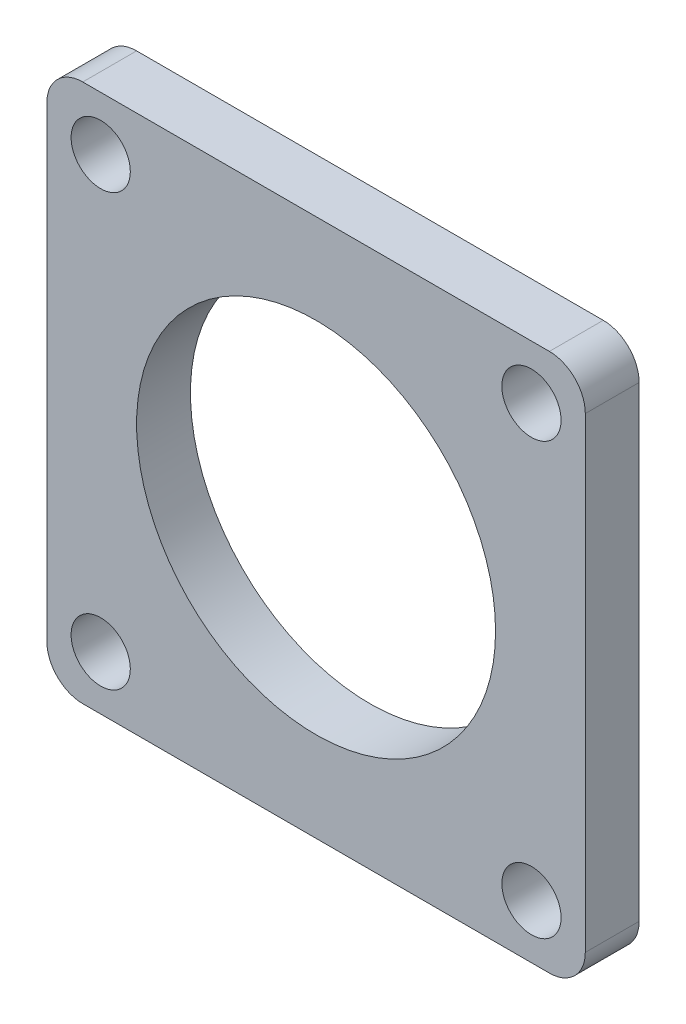
SolidWorks part; units mm, degrees
ref_plane "前视基准面" through (0, 0, 0) normal (0, 0, 1) x (1, 0, 0)
ref_plane "上视基准面" through (0, 0, 0) normal (0, 1, 0) x (1, 0, 0)
ref_plane "右视基准面" through (0, 0, 0) normal (1, 0, 0) x (0, 0, -1)
sketch "草图1" plane through (0, 0, 0) normal (0, 0, 1) x (1, 0, 0)
  line L0 (-15, 0) -> (-15, 15)
  line L1 (-15, 15) -> (0, 15)
  line L2 (15, 0) -> (15, -15)
  line L3 (15, -15) -> (0, -15)
  line L8 (0, 0) -> (15, 0)
  line L9 (0, 0) -> (0, 15)
  line L10 (15, 0) -> (15, 15)
  line L11 (0, 15) -> (15, 15)
  line L12 (0, 0) -> (0, -15)
  line L13 (0, 0) -> (-15, 0)
  line L14 (0, -15) -> (-15, -15)
  line L15 (-15, 0) -> (-15, -15)
  circle A0 centre (0, 0) radius 10
  circle A1 centre (-12, 12) radius 1.65
  circle A2 centre (12, -12) radius 1.65
  circle A3 centre (12, 12) radius 1.65
  circle A4 centre (-12, -12) radius 1.65
extrude "凸台-拉伸1" add sketch "草图1" along normal blind 3 contours A0 L9 L1 L0 L13 A1 | A0 L8 L10 L11 L9 A3 | A0 L13 L15 L14 L12 A4 | A0 L12 L3 L2 L8 A2
fillet "圆角1" radius 2 4 edges at (-15, -15, 1.5) (15, -15, 1.5) (15, 15, 1.5) (-15, 15, 1.5)
